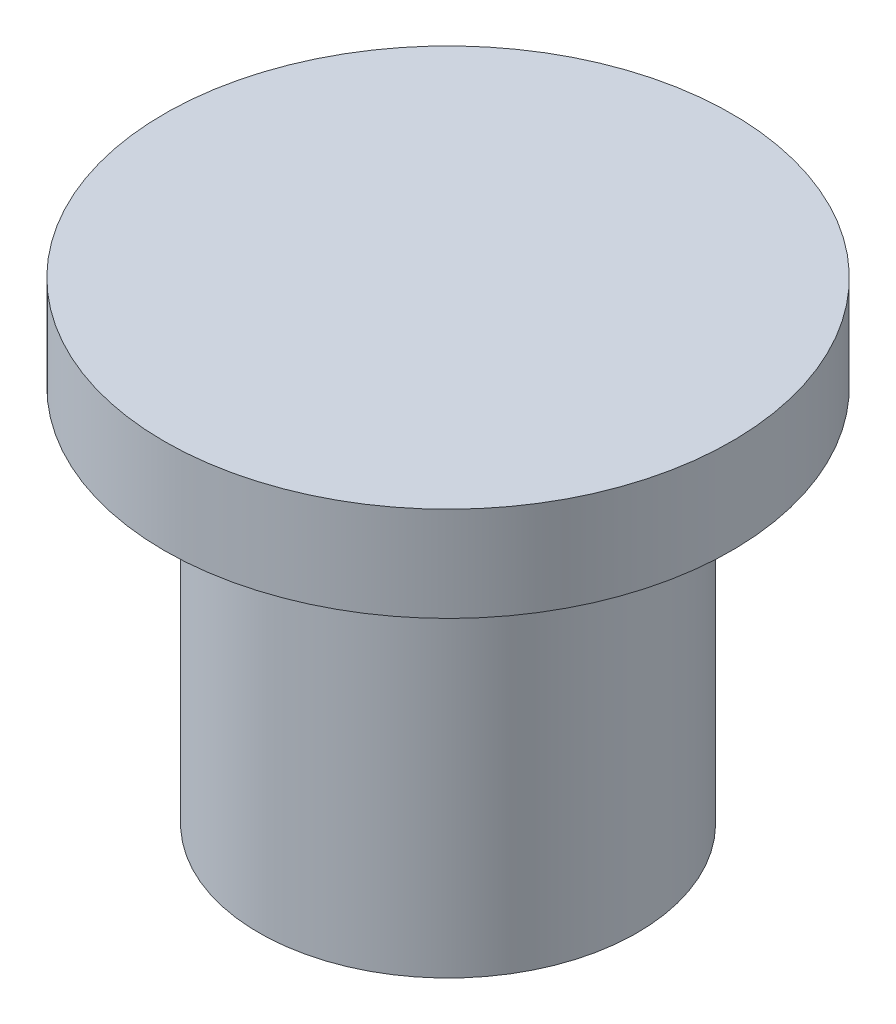
SolidWorks part; units mm, degrees
ref_plane "Front Plane" through (0, 0, 0) normal (0, 0, 1) x (1, 0, 0)
ref_plane "Top Plane" through (0, 0, 0) normal (0, 1, 0) x (1, 0, 0)
ref_plane "Right Plane" through (0, 0, 0) normal (1, 0, 0) x (0, 0, -1)
sketch "Sketch1" plane through (0, 0, 0) normal (0, 1, 0) x (1, 0, 0)
  circle A0 centre (0, 0) radius 7.5
  dimension "D1" = 15
extrude "Boss-Extrude1" add sketch "Sketch1" along normal blind 2.5
sketch "Sketch2" plane through (0, 0, 0) normal (0, -1, 0) x (1, 0, 0)
  circle A0 centre (0, 0) radius 5
  dimension "D1" = 10
extrude "Boss-Extrude2" add sketch "Sketch2" along normal blind 10
